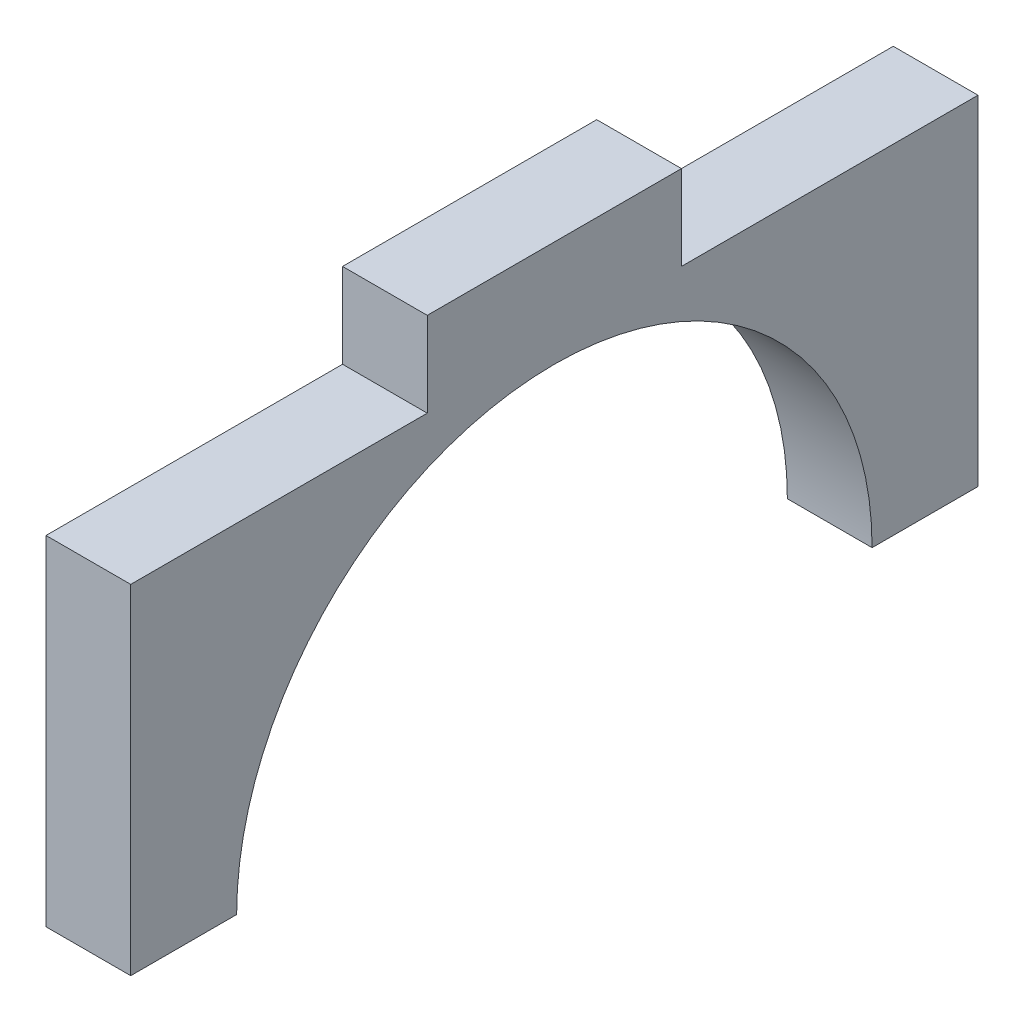
SolidWorks part; units mm, degrees
ref_plane "Front Plane" through (0, 0, 0) normal (0, 0, 1) x (1, 0, 0)
ref_plane "Top Plane" through (0, 0, 0) normal (0, 1, 0) x (1, 0, 0)
ref_plane "Right Plane" through (0, 0, 0) normal (1, 0, 0) x (0, 0, -1)
sketch "Sketch1" plane through (0, 0, 0) normal (1, 0, 0) x (0, 0, -1)
  line L0 (11.1125, 12.7) -> (11.1125, 15.875)
  line L1 (0, 0) -> (3.9688, 0)
  line L2 (0, 0) -> (0, 12.7)
  line L3 (0, 12.7) -> (11.1125, 12.7)
  line L4 (31.75, 0) -> (31.75, 12.7)
  line L5 (11.1125, 15.875) -> (20.6375, 15.875)
  line L6 (20.6375, 15.875) -> (20.6375, 12.7)
  line L7 (15.875, 15.875) -> (15.875, 0) construction
  line L8 (20.6375, 12.7) -> (31.75, 12.7)
  line L9 (27.7813, 0) -> (31.75, 0)
  line L10 (0, 0) -> (31.75, 0) construction
  arc A0 (3.9688, 0) -> (27.7813, 0) centre (15.875, 0) cw
  point P13 (15.875, 0)
  dimension "D5" = 11.9062
  dimension "D1" = 31.75
  dimension "D2" = 12.7
  dimension "D3" = 9.525
  dimension "D4" = 3.175
extrude "Boss-Extrude1" add sketch "Sketch1" along normal blind 3.175
